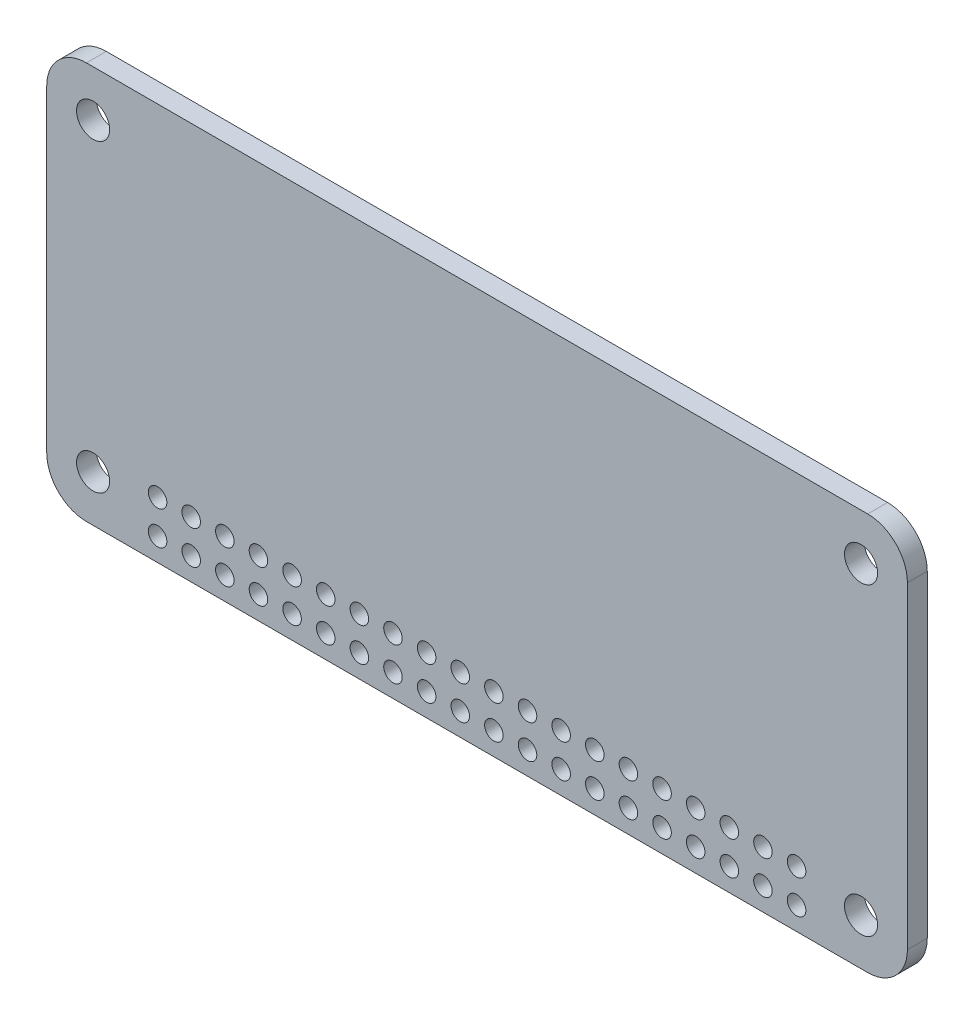
SolidWorks part; units mm, degrees
ref_plane "Alzado" through (0, 0, 0) normal (0, 0, 1) x (1, 0, 0)
ref_plane "Planta" through (0, 0, 0) normal (0, 1, 0) x (1, 0, 0)
ref_plane "Vista lateral" through (0, 0, 0) normal (1, 0, 0) x (0, 0, -1)
sketch "Croquis1" plane through (0, 0, 0) normal (0, 0, 1) x (1, 0, 0)
  line L0 (0, 15) -> (0, -15) construction
  line L1 (29.5, -15) -> (-29.5, -15)
  line L2 (32.5, -12) -> (32.5, 12)
  line L3 (29.5, 15) -> (-29.5, 15)
  line L4 (-32.5, -12) -> (-32.5, 12)
  line L5 (32.5, -15) -> (-32.5, 15) construction
  line L6 (32.5, 15) -> (-32.5, -15) construction
  line L7 (-32.5, 0) -> (32.5, 0) construction
  line L8 (-29.5, -12) -> (29.5, -12) construction
  line L9 (-24.13, -13.27) -> (-24.13, -10.73) construction
  line L10 (-24.13, -10.73) -> (-21.59, -10.73) construction
  line L11 (-24.13, -10.73) -> (24.13, -10.73) construction
  arc A0 (32.5, 12) -> (29.5, 15) centre (29.5, 12) ccw
  arc A1 (29.5, -15) -> (32.5, -12) centre (29.5, -12) ccw
  arc A2 (-29.5, -15) -> (-32.5, -12) centre (-29.5, -12) cw
  arc A3 (-29.5, 15) -> (-32.5, 12) centre (-29.5, 12) ccw
  circle A8 centre (-24.13, -10.73) radius 0.7
  circle A9 centre (-24.13, -13.27) radius 0.7
  circle A10 centre (-21.59, -10.73) radius 0.7
  circle A11 centre (-21.59, -13.27) radius 0.7
  circle A12 centre (-19.05, -10.73) radius 0.7
  circle A13 centre (-19.05, -13.27) radius 0.7
  circle A14 centre (-16.51, -10.73) radius 0.7
  circle A15 centre (-16.51, -13.27) radius 0.7
  circle A16 centre (-13.97, -10.73) radius 0.7
  circle A17 centre (-13.97, -13.27) radius 0.7
  circle A18 centre (-11.43, -10.73) radius 0.7
  circle A19 centre (-11.43, -13.27) radius 0.7
  circle A20 centre (-8.89, -10.73) radius 0.7
  circle A21 centre (-8.89, -13.27) radius 0.7
  circle A22 centre (-6.35, -10.73) radius 0.7
  circle A23 centre (-6.35, -13.27) radius 0.7
  circle A24 centre (-3.81, -10.73) radius 0.7
  circle A25 centre (-3.81, -13.27) radius 0.7
  circle A26 centre (-1.27, -10.73) radius 0.7
  circle A27 centre (-1.27, -13.27) radius 0.7
  circle A28 centre (1.27, -10.73) radius 0.7
  circle A29 centre (1.27, -13.27) radius 0.7
  circle A30 centre (3.81, -10.73) radius 0.7
  circle A31 centre (3.81, -13.27) radius 0.7
  circle A32 centre (6.35, -10.73) radius 0.7
  circle A33 centre (6.35, -13.27) radius 0.7
  circle A34 centre (8.89, -10.73) radius 0.7
  circle A35 centre (8.89, -13.27) radius 0.7
  circle A36 centre (11.43, -10.73) radius 0.7
  circle A37 centre (11.43, -13.27) radius 0.7
  circle A38 centre (13.97, -10.73) radius 0.7
  circle A39 centre (13.97, -13.27) radius 0.7
  circle A40 centre (16.51, -10.73) radius 0.7
  circle A41 centre (16.51, -13.27) radius 0.7
  circle A42 centre (19.05, -10.73) radius 0.7
  circle A43 centre (19.05, -13.27) radius 0.7
  circle A44 centre (21.59, -10.73) radius 0.7
  circle A45 centre (21.59, -13.27) radius 0.7
  circle A46 centre (24.13, -10.73) radius 0.7
  circle A47 centre (24.13, -13.27) radius 0.7
  circle A48 centre (-29, 11.5) radius 1.25
  circle A49 centre (29, 11.5) radius 1.25
  circle A50 centre (29, -11.5) radius 1.25
  circle A51 centre (-29, -11.5) radius 1.25
  point P0 (0, 0)
  point P24 (0, 0)
  point P29 (-24.13, -12)
  point P31 (0, -10.73)
  dimension "D3" = 3
  dimension "D4" = 2.5
  dimension "D6" = 1.4
  dimension "D9" = 3.5
  dimension "D10" = 3.5
  dimension "D1" = 65
  dimension "D2" = 30
  dimension "D5" = 2.54
  dimension "D8" = 2.54
  dimension "D7" = 20
extrude "Saliente-Extruir1" add sketch "Croquis1" along normal blind 1.5
